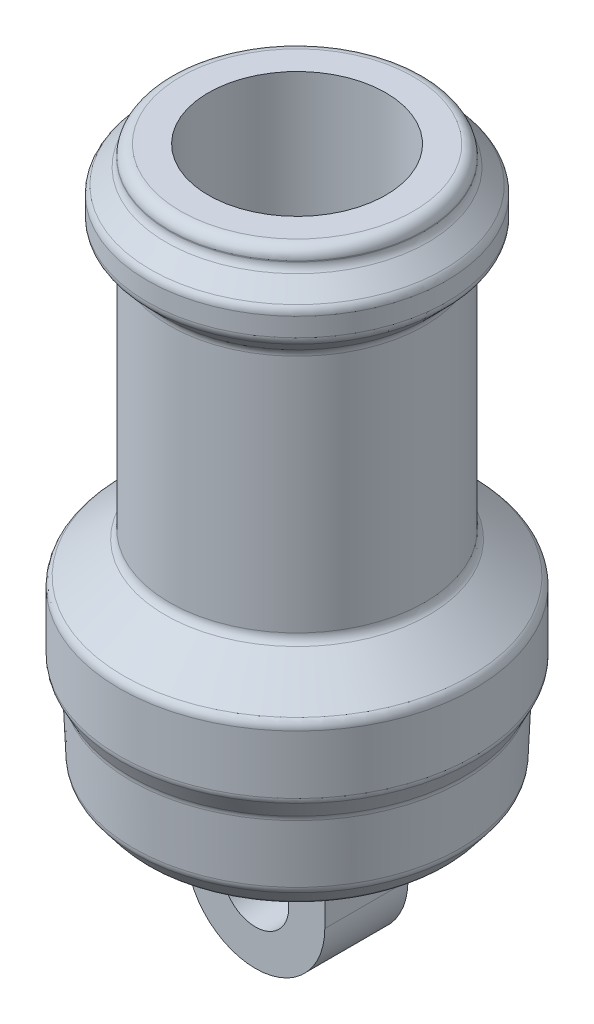
SolidWorks part; units mm, degrees
material "7050-T7651"
ref_plane "Спереди" through (0, 0, 0) normal (0, 0, 1) x (1, 0, 0)
ref_plane "Сверху" through (0, 0, 0) normal (0, 1, 0) x (1, 0, 0)
ref_plane "Справа" through (0, 0, 0) normal (1, 0, 0) x (0, 0, -1)
sketch "Эскиз1" plane through (0, 0, 0) normal (0, 0, 1) x (1, 0, 0)
  line L0 (-16, 50) -> (-16, -43.634)
  line L1 (-32, 50) -> (32, 50) construction
  line L2 (-32, 50) -> (-32, -50) construction
  line L3 (-32, -50) -> (32, -50) construction
  line L4 (32, 50) -> (32, -50) construction
  line L5 (0, -50) -> (0, 50) construction
  line L6 (-32, 0) -> (32, 0) construction
  line L7 (-16, -43.634) -> (0, -43.634)
  line L8 (-16, 50) -> (-23, 50)
  line L9 (-23, 50) -> (-23, -43.3209) construction
  line L10 (-32, -30.0685) -> (-29.926, -34.0685)
  line L11 (-32, -18.0685) -> (-32, -30.0685)
  line L14 (-23, 50) -> (-23, 47)
  line L15 (-23, 47) -> (-27, 43)
  line L16 (-27, 43) -> (-27, 38)
  line L17 (-27, 38) -> (-23, 33.9315)
  line L18 (-23, 33.9315) -> (-23, -11.0685)
  line L19 (-23, -11.0685) -> (-32, -18.0685)
  line L20 (0, -43.634) -> (0, -50)
  line L21 (0, -43.634) -> (0, -50)
  line L22 (-29.926, -34.0685) -> (-29.44, -45.8822)
  line L23 (-29.44, -45.8822) -> (-26.2373, -50)
  line L24 (-26.2373, -50) -> (0, -50)
  point P0 (0, 0)
  dimension "D1" = 16
  dimension "D5" = 27
  dimension "D2" = 7
  dimension "D3" = 100
  dimension "D4" = 32
  dimension "D6" = 3
  dimension "D7" = 12
  dimension "D8" = 7
  dimension "D9" = 5
  dimension "D10" = 4
  dimension "D11" = 4.0685
  dimension "D12" = 45
  dimension "D13" = 4
revolve "Повернуть2" add sketch "Эскиз1" angle 360 about L5
sketch "Эскиз2" plane through (0, -50, 0) normal (0, -1, 0) x (-1, 0, 0)
  line L1 (12.5, -7.5) -> (-12.5, -7.5)
  line L2 (12.5, -7.5) -> (12.5, 7.5)
  line L3 (12.5, 7.5) -> (-12.5, 7.5)
  line L4 (-12.5, -7.5) -> (-12.5, 7.5)
  line L5 (0, 7.5) -> (0, -7.5) construction
  line L6 (12.5, 0) -> (-12.5, 0) construction
  point P0 (0, 0)
  dimension "D1" = 25
  dimension "D2" = 15
extrude "Бобышка-Вытянуть1" add sketch "Эскиз2" along normal blind 25
sketch "Эскиз3" plane through (0, 0, -7.5) normal (0, 0, -1) x (-1, 0, 0)
  line L0 (12.5, -75) -> (12.5, -50) construction
  line L1 (-12.5, -75) -> (-12.5, -50) construction
  line L2 (12.5, -62.5) -> (18.1031, -62.5)
  line L3 (18.1031, -62.5) -> (18.1031, -97.8203)
  line L4 (18.1031, -97.8203) -> (-20.0392, -97.8203)
  line L5 (-20.0392, -97.8203) -> (-20.0392, -62.5)
  line L6 (-20.0392, -62.5) -> (-12.5, -62.5)
  arc A0 (12.5, -62.5) -> (-12.5, -62.5) centre (0, -62.5) cw
  circle A1 centre (0, -62.5) radius 6
extrude "Вырез-Вытянуть1" cut sketch "Эскиз3" against normal through all
fillet "Скругление1" radius 2 4 edges at (-12.5, -50, 0) (0, -50, 7.5) (12.5, -50, 0) (0, -50, -7.5)
fillet "Скругление2" radius 2 9 edges at (0, -50, -26.2373) (0, -45.8822, -29.44) (0, -34.0685, -29.926) (0, -30.0685, -32) (0, -18.0685, -32) (0, -11.0685, -23) (0, 47, -23) (0, 43, -27) (0, 38, -27)
fillet "Скругление3" radius 2 2 edges at (0, 50, -23) (0, 33.9315, -23)
